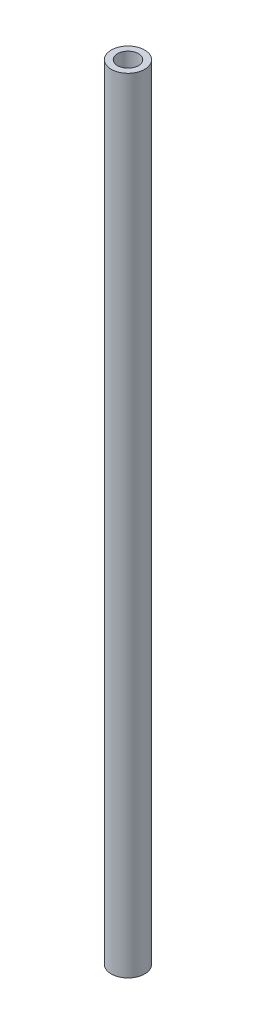
SolidWorks part; units mm, degrees
ref_plane "Front Plane" through (0, 0, 0) normal (0, 0, 1) x (1, 0, 0)
ref_plane "Top Plane" through (0, 0, 0) normal (0, 1, 0) x (1, 0, 0)
ref_plane "Right Plane" through (0, 0, 0) normal (1, 0, 0) x (0, 0, -1)
sketch "Sketch1" plane through (0, 0, 0) normal (0, 1, 0) x (1, 0, 0)
  circle A0 centre (0, 0) radius 3.2
extrude "Boss-Extrude1" add sketch "Sketch1" along normal blind 150
sketch "Sketch2" plane through (0, 150, 0) normal (0, 1, 0) x (1, 0, 0)
  circle A0 centre (0, 0) radius 2
  dimension "D1" = 4
extrude "Cut-Extrude1" cut sketch "Sketch2" against normal blind 12.5
sketch "Sketch3" plane through (0, 0, 0) normal (0, -1, 0) x (1, 0, 0)
  circle A0 centre (0, 0) radius 2
  dimension "D1" = 4
extrude "Cut-Extrude2" cut sketch "Sketch3" against normal blind 12.5
